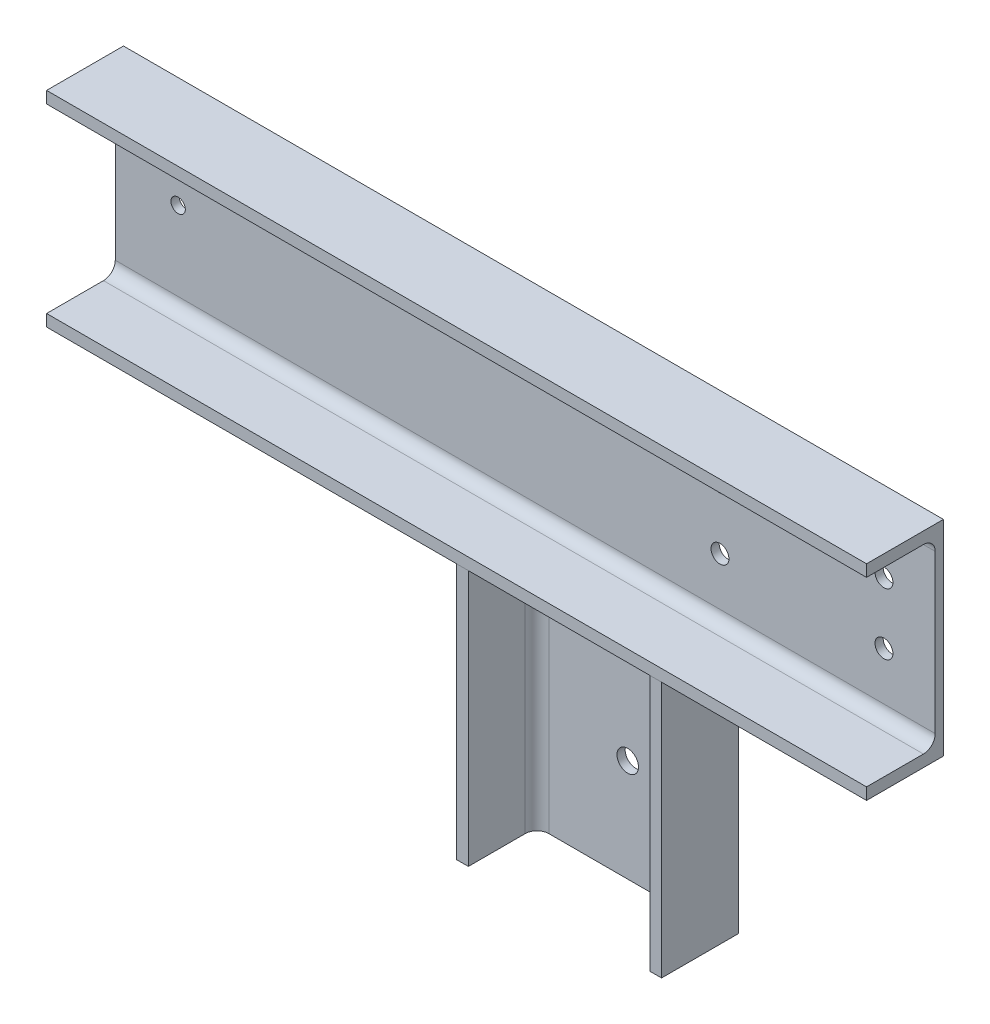
SolidWorks part; units mm, degrees
other "DetailItem1"
other "Weld Folder"
other "Weld Bead1"
ref_plane "Front Plane" through (0, 0, 0) normal (0, 0, 1) x (1, 0, 0)
ref_plane "Top Plane" through (0, 0, 0) normal (0, 1, 0) x (1, 0, 0)
ref_plane "Right Plane" through (0, 0, 0) normal (1, 0, 0) x (0, 0, -1)
sketch "Sketch1" plane through (0, 0, 0) normal (0, 0, 1) x (1, 0, 0)
  line L0 (400, 0) -> (-400, 0)
  line L1 (100, 0) -> (100, -250)
  point P4 (0, 0)
  dimension "D1" = 800
  dimension "D2" = 250
  dimension "D3" = 300
other "Square hss AL CS CHANNEL SQR END 4 X 2.02(1)"
ref_plane "Plane1" through (400, 0, 0) normal (-1, 0, 0) x (0, 0, 1)
sketch "Sketch11" plane through (400, 0, 0) normal (-1, 0, 0) x (0, 0, 1)
  line L0 (0, 0) -> (0, 200)
  line L1 (0, 100) -> (8, 100) construction
  line L2 (8, 177) -> (8, 23)
  line L3 (19.5, 11.5) -> (75, 11.5)
  line L5 (75, 0) -> (0, 0)
  line L6 (75, 200) -> (0, 200)
  line L7 (75, 0) -> (75, 11.5)
  line L8 (75, 200) -> (75, 188.5)
  line L9 (19.5, 188.5) -> (75, 188.5)
  arc A0 (8, 177) -> (19.5, 188.5) centre (19.5, 177) cw
  arc A2 (19.5, 11.5) -> (8, 23) centre (19.5, 23) cw
  point P2 (4, 100)
  point P5 (0, 0)
  point P15 (37.5, 200)
  point P17 (37.5, 0)
  dimension "Radius_1" = 11.5
  dimension "Thickness" = 11.5
  dimension "H_Leg" = 75
  dimension "tw" = 8
  dimension "V_Leg" = 200
other "Square hss AL CS CHANNEL SQR END 4 X 2.02(2)"
ref_plane "Plane2" through (200, 0, 0) normal (0, -1, 0) x (0, 0, 1)
sketch "Sketch12" plane through (200, 0, 0) normal (0, -1, 0) x (0, 0, 1)
  line L0 (0, 0) -> (0, 200)
  line L1 (0, 100) -> (8, 100) construction
  line L2 (8, 177) -> (8, 23)
  line L3 (19.5, 11.5) -> (75, 11.5)
  line L5 (75, 0) -> (0, 0)
  line L6 (75, 200) -> (0, 200)
  line L7 (75, 0) -> (75, 11.5)
  line L8 (75, 200) -> (75, 188.5)
  line L9 (19.5, 188.5) -> (75, 188.5)
  arc A0 (8, 177) -> (19.5, 188.5) centre (19.5, 177) cw
  arc A2 (19.5, 11.5) -> (8, 23) centre (19.5, 23) cw
  point P2 (4, 100)
  point P5 (0, 0)
  point P15 (37.5, 200)
  point P17 (37.5, 0)
  dimension "Radius_1" = 11.5
  dimension "Thickness" = 11.5
  dimension "H_Leg" = 75
  dimension "tw" = 8
  dimension "V_Leg" = 200
sketch "Sketch13" plane through (0, 0, 8) normal (0, 0, 1) x (1, 0, 0)
  line L0 (100, 0) -> (100, -250) construction
  line L1 (-400, 0) -> (400, 0) construction
  point P0 (100, -150)
  dimension "D1" = 150
hole_wizard "M24x3.0 Tapped Hole1" positions "Sketch14" profile "Sketch15" tap size "M24x3.0" standard "ANSI Metric" end condition through all
sketch "Sketch14" plane through (0, 0, 8) normal (0, 0, 1) x (1, 0, 0)
  point P0 (100, -150)
sketch "Sketch15" plane through (100, -150, 8) normal (1, 0, 0) x (0, -1, 0)
  line L0 (0, 0) -> (0, 8)
  line L1 (0, 8) -> (10.5, 8)
  line L2 (10.5, 8) -> (10.5, 0)
  line L5 (10.5, 0) -> (0, 0)
  line L11 (0, -6.35) -> (0, 107.95) construction
  dimension "Thru Tap Drill Dia." = 21
  dimension "Thru Tap Drill Depth" = 8
sketch "Sketch20" plane through (0, 0, 8) normal (0, 0, 1) x (1, 0, 0)
  line L1 (-400, 23) -> (-400, 177) construction
  line L2 (-400, 100) -> (-343.91, 100) construction
  point P0 (-343.91, 100)
  dimension "D2" = 56.09
hole_wizard "M20x2.0 Tapped Hole1" positions "Sketch21" profile "Sketch22" tap size "M16x2.0" standard "ANSI Metric" end condition through all
sketch "Sketch21" plane through (0, 0, 8) normal (0, 0, 1) x (1, 0, 0)
  point P3 (-338.672, 100)
sketch "Sketch22" plane through (-338.672, 100, 8) normal (1, 0, 0) x (0, -1, 0)
  line L0 (0, 0) -> (0, 8)
  line L1 (0, 8) -> (7, 8)
  line L2 (7, 8) -> (7, 0)
  line L5 (7, 0) -> (0, 0)
  line L11 (0, -6.35) -> (0, 107.95) construction
  dimension "Thru Tap Drill Dia." = 14
  dimension "Thru Tap Drill Depth" = 8
sketch "Sketch23" plane through (0, 0, 0) normal (0, -1, 0) x (1, 0, 0)
  line L0 (177, 8) -> (23, 8) construction
  line L1 (11.5, 19.5) -> (11.5, 75) construction
  line L2 (11.5, 75) -> (0, 75) construction
  line L3 (0, 75) -> (0, 0) construction
  line L4 (0, 0) -> (200, 0) construction
  line L5 (200, 0) -> (200, 75) construction
  line L6 (200, 75) -> (188.5, 75) construction
  line L7 (188.5, 75) -> (188.5, 19.5) construction
  line L8 (177, 8) -> (23, 8)
  line L9 (11.5, 19.5) -> (11.5, 75)
  line L10 (11.5, 75) -> (0, 75)
  line L11 (0, 75) -> (0, 0)
  line L12 (0, 0) -> (200, 0)
  line L13 (200, 0) -> (200, 75)
  line L14 (200, 75) -> (188.5, 75)
  line L15 (188.5, 75) -> (188.5, 19.5)
  arc A0 (11.5, 19.5) -> (23, 8) centre (23, 19.5) ccw construction
  arc A1 (177, 8) -> (188.5, 19.5) centre (177, 19.5) ccw construction
  arc A2 (11.5, 19.5) -> (23, 8) centre (23, 19.5) ccw
  arc A3 (177, 8) -> (188.5, 19.5) centre (177, 19.5) ccw
sketch "Sketch24" plane through (0, 0, 8) normal (0, 0, 1) x (1, 0, 0)
  line L0 (400, 100) -> (350, 100) construction
  line L1 (350, 130) -> (190, 130)
  line L2 (350, 130) -> (350, 70)
  line L3 (350, 70) -> (190, 70)
  line L4 (190, 130) -> (190, 70)
  line L5 (400, 23) -> (400, 177) construction
  dimension "D1" = 50
  dimension "D2" = 160
  dimension "D3" = 60
hole_wizard "M20x2.5 Tapped Hole1" positions "Sketch25" profile "Sketch26" tap size "M20x2.5" standard "ANSI Metric"
sketch "Sketch25" plane through (0, 0, 8) normal (0, 0, 1) x (1, 0, 0)
  point P0 (190, 130)
  point P3 (350, 130)
  point P6 (350, 70)
  point P9 (190, 70)
sketch "Sketch26" plane through (190, 130, 8) normal (1, 0, 0) x (0, -1, 0)
  line L0 (0, 0) -> (0, 52.7575)
  line L1 (0, 52.7575) -> (8.75, 47.5)
  line L2 (8.75, 47.5) -> (8.75, 0)
  line L5 (8.75, 0) -> (0, 0)
  line L10 (0, 52.7575) -> (-8.75, 47.5) construction
  line L11 (0, -6.35) -> (0, 107.95) construction
  dimension "Tap Drill Dia." = 17.5
  dimension "Tap Drill Depth" = 47.5
  dimension "Drill Angle" = 118
